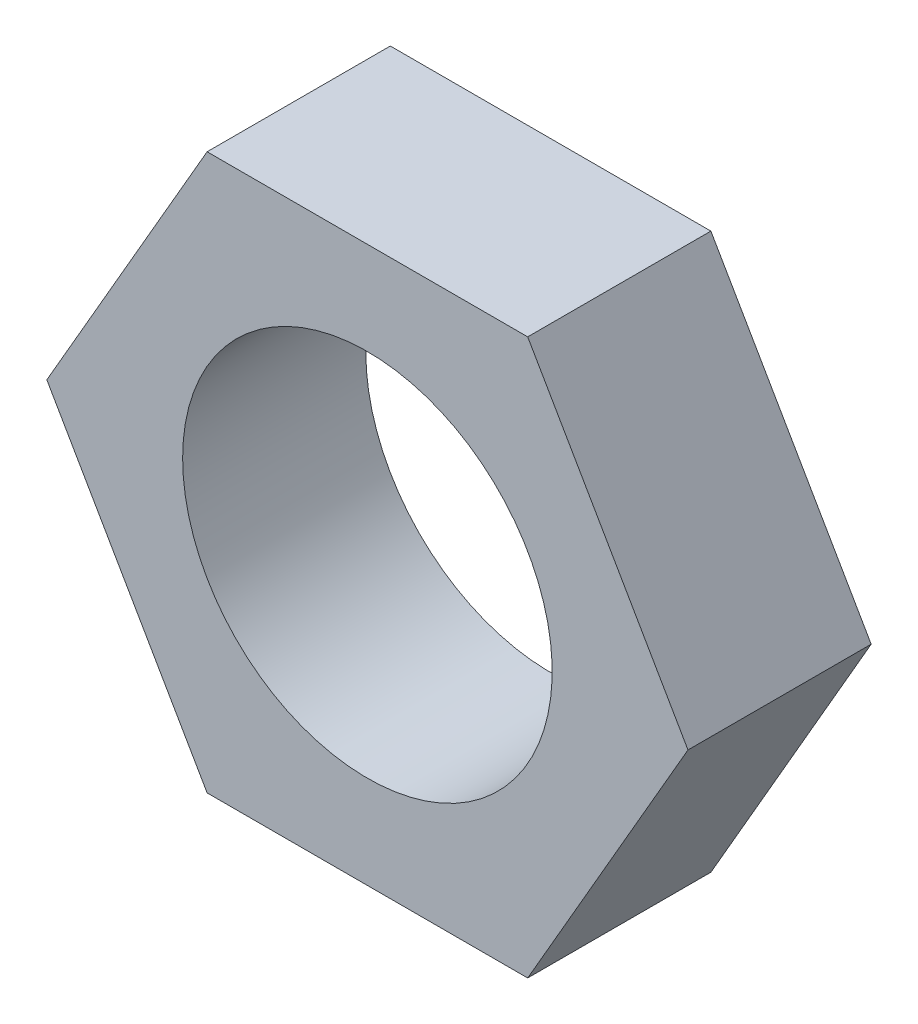
SolidWorks part; units mm, degrees
ref_plane "Front Plane" through (0, 0, 0) normal (0, 0, 1) x (1, 0, 0)
ref_plane "Top Plane" through (0, 0, 0) normal (0, 1, 0) x (1, 0, 0)
ref_plane "Right Plane" through (0, 0, 0) normal (1, 0, 0) x (0, 0, -1)
sketch "Sketch1" plane through (0, 0, 0) normal (0, 0, 1) x (1, 0, 0)
  line L1 (22.225, 0) -> (11.1125, 19.2474)
  line L2 (11.1125, 19.2474) -> (-11.1125, 19.2474)
  line L3 (-11.1125, 19.2474) -> (-22.225, 0)
  line L4 (-22.225, 0) -> (-11.1125, -19.2474)
  line L5 (-11.1125, -19.2474) -> (11.1125, -19.2474)
  line L6 (11.1125, -19.2474) -> (22.225, 0)
  circle A0 centre (0, 0) radius 19.2474 construction
  dimension "D1" = 44.45
extrude "Boss-Extrude1" add sketch "Sketch1" along normal blind 12.7
sketch "Sketch2" plane through (0, 0, 0) normal (0, 0, -1) x (-1, 0, 0)
  circle A0 centre (0, 0) radius 12.8107
extrude "Cut-Extrude1" cut sketch "Sketch2" against normal blind 12.7
